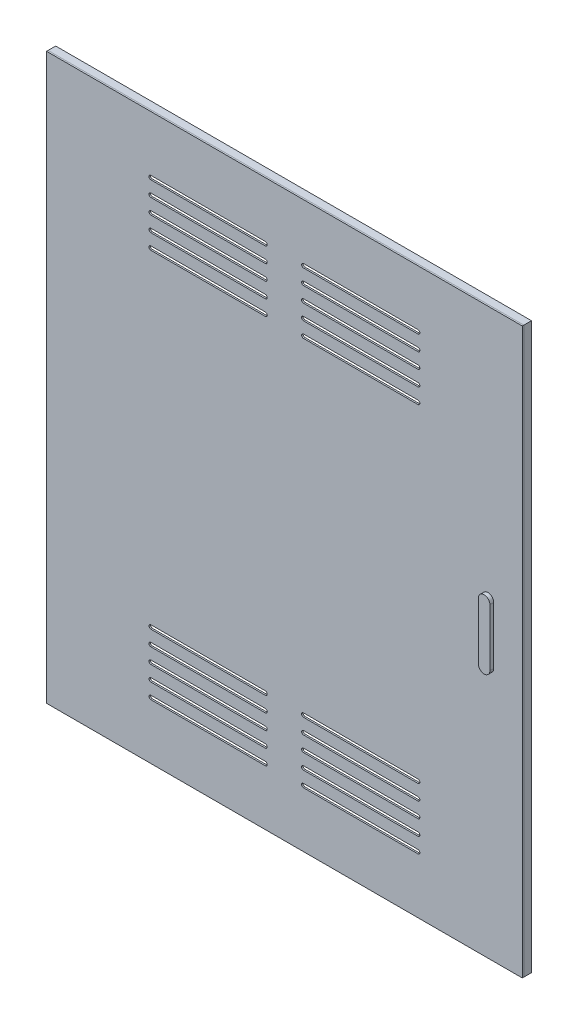
SolidWorks part; units mm, degrees
material "Plain Carbon Steel"
ref_plane "Front Plane" through (0, 0, 0) normal (0, 0, 1) x (1, 0, 0)
ref_plane "Top Plane" through (0, 0, 0) normal (0, 1, 0) x (1, 0, 0)
ref_plane "Right Plane" through (0, 0, 0) normal (1, 0, 0) x (0, 0, -1)
sketch "Sketch1" plane through (0, 0, 0) normal (0, 0, 1) x (1, 0, 0)
  line L0 (-603.5, 720) -> (-603.5, -720)
  line L1 (-623.5, 740) -> (623.5, 740)
  line L2 (-623.5, 740) -> (-623.5, -740)
  line L3 (-623.5, -740) -> (623.5, -740)
  line L4 (623.5, 740) -> (623.5, -740)
  line L5 (-603.5, -720) -> (603.5, -720)
  line L6 (603.5, 720) -> (603.5, -720)
  line L7 (-603.5, 720) -> (603.5, 720)
  line L8 (0, 0) -> (0, 740) construction
  line L9 (0, 0) -> (0, -740) construction
  dimension "D2" = 1480
  dimension "D3" = 1247
  dimension "D1" = 20
extrude "Boss-Extrude1" add sketch "Sketch1" along normal blind 20
sketch "Sketch3" plane through (-623.5, 0, 0) normal (-1, 0, 0) x (0, 0, 1)
  line L0 (20, 740) -> (20, -740) construction
  line L1 (20, 560) -> (0, 560)
  line L2 (20, 560) -> (20, 500)
  line L3 (20, 500) -> (0, 500)
  line L4 (0, 560) -> (0, 500)
  line L5 (0, 500) -> (0, 0) construction
  line L6 (20, -500) -> (0, -500) construction
  line L7 (20, -500) -> (20, -560) construction
  line L8 (20, -560) -> (0, -560) construction
  line L9 (0, -500) -> (0, -560) construction
  line L10 (0, 0) -> (0, -500) construction
  line L11 (0, 740) -> (0, -740) construction
  dimension "D1" = 60
  dimension "D2" = 1000
  dimension "D3" = 20
extrude "Boss-Extrude2" add sketch "Sketch3" along normal blind 2
sketch "Sketch4" plane through (0, 560, 0) normal (0, 1, 0) x (1, 0, 0)
  line L0 (-630.5, 0) -> (-625.5, 0) construction
  line L1 (-623.5, -20) -> (-623.5, 0) construction
  circle A0 centre (-630.5, 0) radius 7
  circle A1 centre (-630.5, 0) radius 5
  dimension "D1" = 10
extrude "Boss-Extrude3" add sketch "Sketch4" against normal up to surface (60 mm away) up to face at (-625, 500, 7.5)
mirror "Mirror1" about plane through (0, 0, 0) normal (0, 1, 0) of "Boss-Extrude3", "Boss-Extrude2"
sketch "Sketch5" plane through (0, 0, 20) normal (0, 0, 1) x (1, 0, 0)
  line L1 (-623.5, 740) -> (623.5, 740)
  line L2 (-623.5, 740) -> (-623.5, -740)
  line L3 (-623.5, -740) -> (623.5, -740)
  line L4 (623.5, 740) -> (623.5, -740)
extrude "Boss-Extrude4" add sketch "Sketch5" along normal blind 4 separate body
sketch "Sketch6" plane through (0, 0, 24) normal (0, 0, 1) x (1, 0, 0)
  line L0 (533.5, 75) -> (533.5, -75) construction
  line L1 (548.5, 75) -> (548.5, -75)
  line L2 (518.5, 75) -> (518.5, -75)
  line L4 (623.5, -740) -> (623.5, 740) construction
  line L5 (0, 0) -> (533.5, 0) construction
  arc A0 (548.5, 75) -> (518.5, 75) centre (533.5, 75) ccw
  arc A1 (518.5, -75) -> (548.5, -75) centre (533.5, -75) ccw
  point P2 (533.5, 0)
  dimension "D1" = 150
  dimension "D2" = 30
  dimension "D4" = 75
extrude "Boss-Extrude5" add sketch "Sketch6" along normal blind 10
sketch "Sketch7" plane through (0, 0, 24) normal (0, 0, 1) x (1, 0, 0)
  line L0 (-350, 590) -> (-50, 590) construction
  line L1 (-350, 595) -> (-50, 595)
  line L2 (-350, 585) -> (-50, 585)
  line L3 (50, 590) -> (350, 590) construction
  line L4 (50, 595) -> (350, 595)
  line L5 (50, 585) -> (350, 585)
  line L6 (-50, 590) -> (50, 590) construction
  line L7 (0, 740) -> (0, 590) construction
  line L8 (623.5, 740) -> (-623.5, 740) construction
  arc A0 (-350, 595) -> (-350, 585) centre (-350, 590) ccw
  arc A1 (-50, 585) -> (-50, 595) centre (-50, 590) ccw
  arc A2 (50, 595) -> (50, 585) centre (50, 590) ccw
  arc A3 (350, 585) -> (350, 595) centre (350, 590) ccw
  point P2 (-200, 590)
  point P7 (200, 590)
  dimension "D1" = 10
  dimension "D2" = 100
  dimension "D3" = 300
  dimension "D4" = 150
extrude "Cut-Extrude1" cut sketch "Sketch7" against normal through all
pattern_linear "LPattern1" count 5 spacing 40 along (0, -1, 0) of "Cut-Extrude1"
mirror "Mirror2" about plane through (0, 0, 0) normal (0, 1, 0) of "LPattern1", "Cut-Extrude1"
